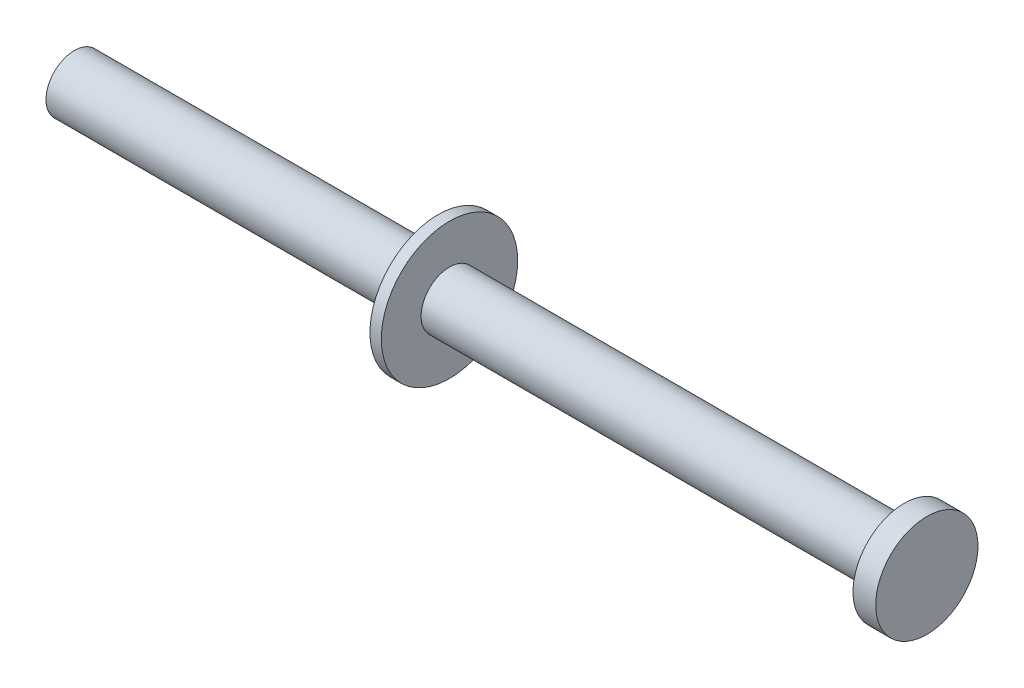
SolidWorks part; units mm, degrees
ref_plane "Front Plane" through (0, 0, 0) normal (0, 0, 1) x (1, 0, 0)
ref_plane "Top Plane" through (0, 0, 0) normal (0, 1, 0) x (1, 0, 0)
ref_plane "Right Plane" through (0, 0, 0) normal (1, 0, 0) x (0, 0, -1)
sketch "Sketch2" plane through (0, 0, 0) normal (1, 0, 0) x (0, 0, -1)
  circle A0 centre (0, 0) radius 9
  dimension "D1" = 18
extrude "Boss-Extrude1" add sketch "Sketch2" along normal blind 4
sketch "Sketch3" plane through (0, 0, 0) normal (-1, 0, 0) x (0, 0, 1)
  circle A0 centre (0, 0) radius 5
  dimension "D1" = 10
extrude "Boss-Extrude2" add sketch "Sketch3" along normal blind 146
ref_plane "Plane1" through (-80, 0, 0) normal (1, 0, 0) x (0, 0, -1)
sketch "Sketch4" plane through (-80, 0, 0) normal (1, 0, 0) x (0, 0, -1)
  circle A0 centre (0, 0) radius 12
  dimension "D1" = 24
extrude "Boss-Extrude3" add sketch "Sketch4" against normal blind 2
